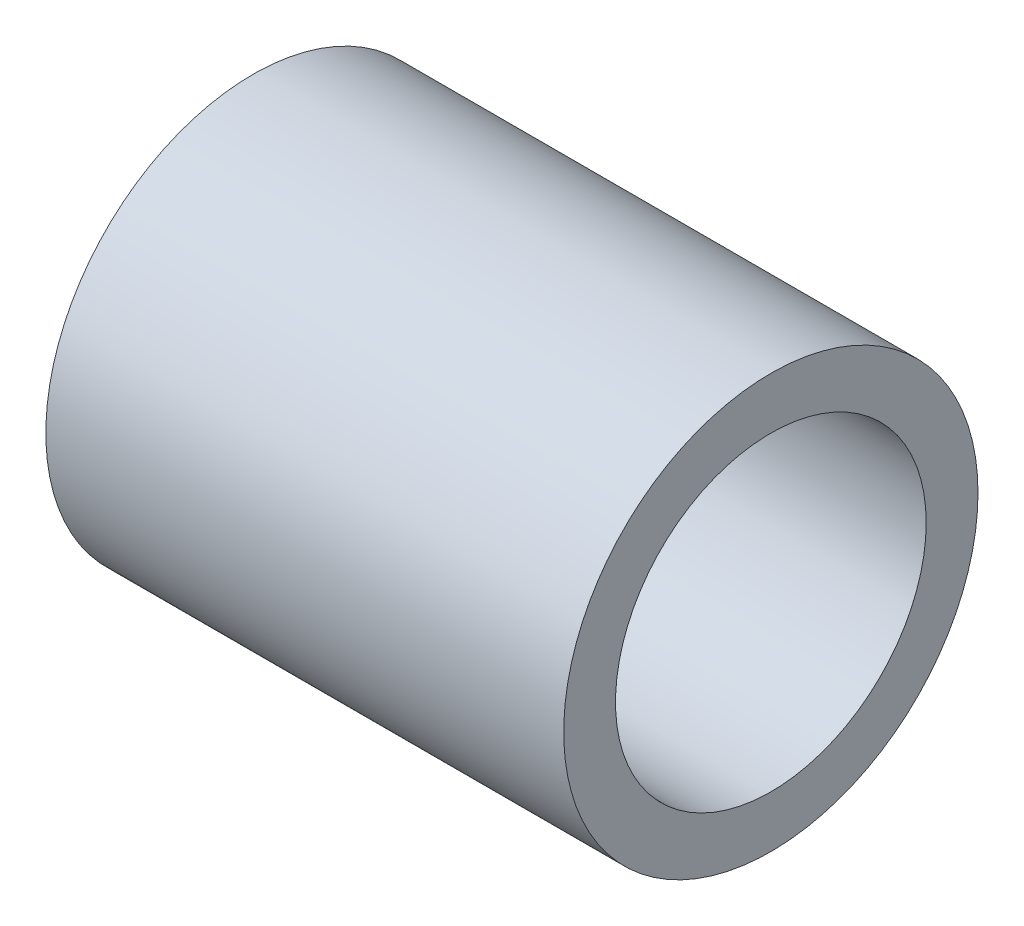
SolidWorks part; units mm, degrees
ref_plane "Front Plane" through (0, 0, 0) normal (0, 0, 1) x (1, 0, 0)
ref_plane "Top Plane" through (0, 0, 0) normal (0, 1, 0) x (1, 0, 0)
ref_plane "Right Plane" through (0, 0, 0) normal (1, 0, 0) x (0, 0, -1)
ref_plane "Plane1" through (521, 0, 0) normal (1, 0, 0) x (0, 0, -1)
sketch "Sketch1" plane through (521, 0, 0) normal (1, 0, 0) x (0, 0, -1)
  circle A0 centre (-157, 300) radius 8
extrude "Boss-Extrude1" add sketch "Sketch1" along normal blind 20
sketch "Sketch2" plane through (541, 0, 0) normal (1, 0, 0) x (0, 0, -1)
  circle A0 centre (-157, 300) radius 6
extrude "Cut-Extrude1" cut sketch "Sketch2" against normal blind 40
